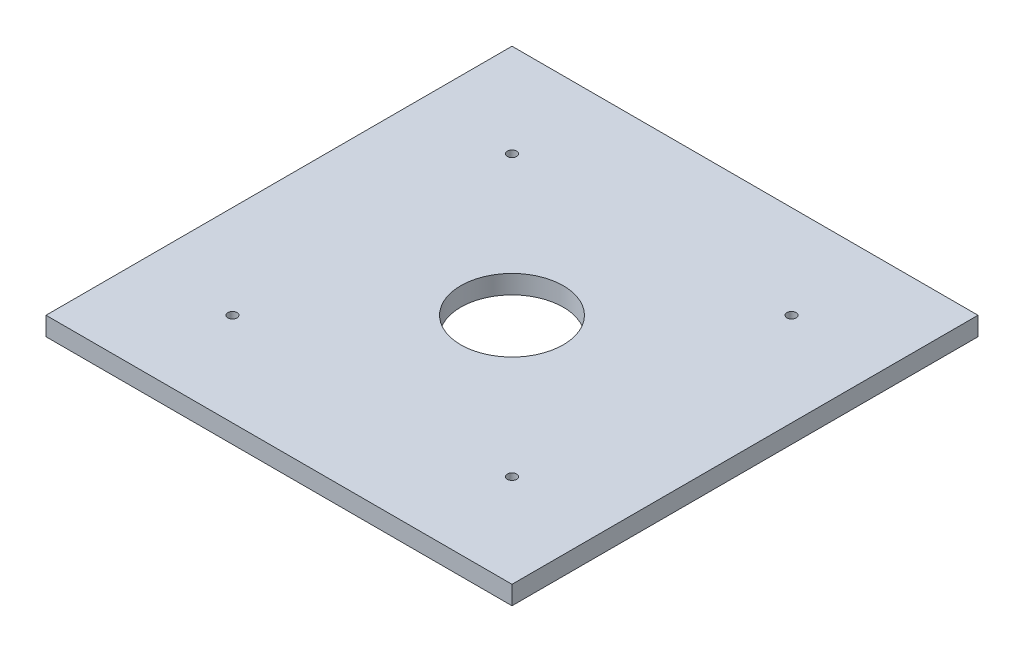
SolidWorks part; units mm, degrees
ref_plane "Front Plane" through (0, 0, 0) normal (0, 0, 1) x (1, 0, 0)
ref_plane "Top Plane" through (0, 0, 0) normal (0, 1, 0) x (1, 0, 0)
ref_plane "Right Plane" through (0, 0, 0) normal (1, 0, 0) x (0, 0, -1)
sketch "Sketch1" plane through (0, 0, 0) normal (0, 1, 0) x (1, 0, 0)
  line L1 (-250, -250) -> (250, -250)
  line L2 (-250, -250) -> (-250, 250)
  line L3 (-250, 250) -> (250, 250)
  line L4 (250, -250) -> (250, 250)
  line L5 (-250, -250) -> (250, 250) construction
  line L6 (-250, 250) -> (250, -250) construction
  line L7 (150, -150) -> (-150, -150) construction
  line L8 (150, -150) -> (150, 150) construction
  line L9 (150, 150) -> (-150, 150) construction
  line L10 (-150, -150) -> (-150, 150) construction
  line L11 (150, -150) -> (-150, 150) construction
  line L12 (150, 150) -> (-150, -150) construction
  circle A0 centre (0, 0) radius 55
  circle A1 centre (-150, 150) radius 5
  circle A2 centre (150, 150) radius 5
  circle A3 centre (-150, -150) radius 5
  circle A4 centre (150, -150) radius 5
  point P0 (0, 0)
  dimension "D2" = 110
  dimension "D4" = 10
  dimension "D1" = 500
  dimension "D3" = 300
extrude "Boss-Extrude1" add sketch "Sketch1" along normal mid plane 20
